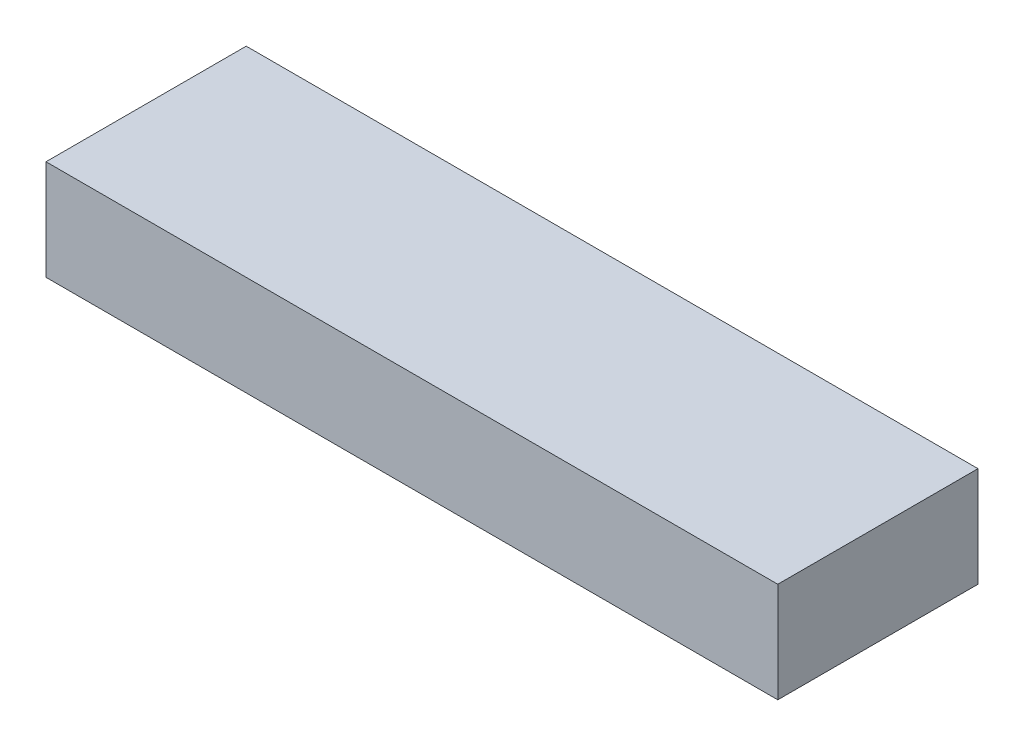
SolidWorks part; units mm, degrees
ref_plane "Front Plane" through (0, 0, 0) normal (0, 0, 1) x (1, 0, 0)
ref_plane "Top Plane" through (0, 0, 0) normal (0, 1, 0) x (1, 0, 0)
ref_plane "Right Plane" through (0, 0, 0) normal (1, 0, 0) x (0, 0, -1)
sketch "Sketch1" plane through (0, 0, 0) normal (0, 1, 0) x (1, 0, 0)
  line L1 (0, 0) -> (73.1, 0)
  line L2 (0, 0) -> (0, 20)
  line L3 (0, 20) -> (73.1, 20)
  line L4 (73.1, 0) -> (73.1, 20)
extrude "Boss-Extrude1" add sketch "Sketch1" along normal blind 10
